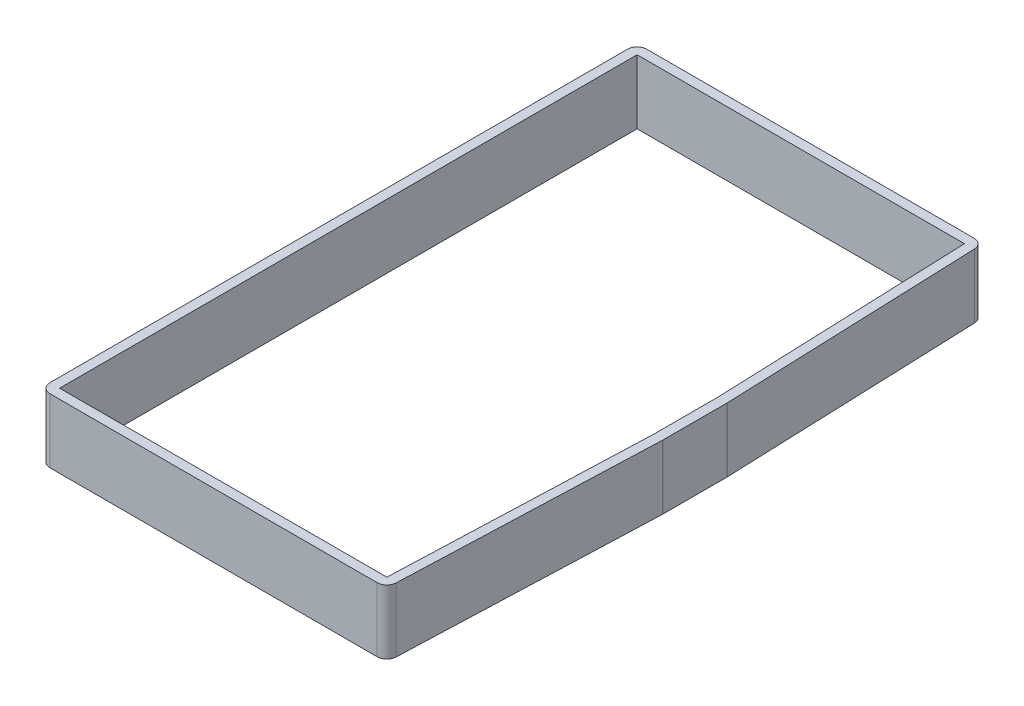
SolidWorks part; units mm, degrees
ref_plane "Front Plane" through (0, 0, 0) normal (0, 0, 1) x (1, 0, 0)
ref_plane "Top Plane" through (0, 0, 0) normal (0, 1, 0) x (1, 0, 0)
ref_plane "Right Plane" through (0, 0, 0) normal (1, 0, 0) x (0, 0, -1)
sketch "Sketch1" plane through (0, 0, 0) normal (0, 1, 0) x (1, 0, 0)
  line L0 (-51, 90) -> (51, 90)
  line L1 (-51, 90) -> (-51, -90)
  line L2 (51, -90) -> (54, -10)
  line L3 (-51, -90) -> (51, -90)
  line L4 (-51, 90) -> (51, -90) construction
  line L5 (51, 90) -> (-51, -90) construction
  line L6 (54, -10) -> (54, 10)
  line L7 (54, 10) -> (51, 90)
  point P1 (0, 0)
  dimension "D1" = 20
  dimension "D2" = 3
  dimension "D3" = 102
  dimension "D4" = 180
extrude "Extrude-Thin1" add sketch "Sketch1" along normal mid plane 20 thin thin type one direction wall 3
fillet "Fillet1" radius 3 6 edges at (-54, 0, -93) (53.8896, 0, -93) (57, 0, -10.0562) (57, 0, 10.0562) (53.8896, 0, 93) (-54, 0, 93)
